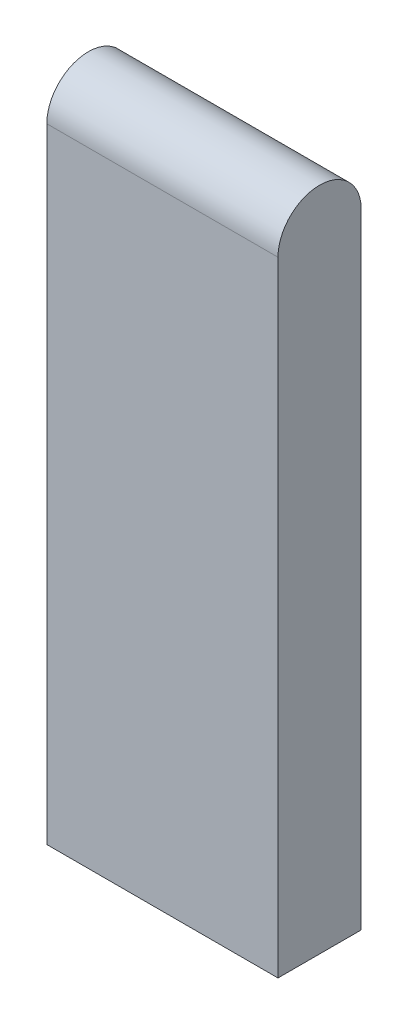
SolidWorks part; units mm, degrees
ref_plane "Front Plane" through (0, 0, 0) normal (0, 0, 1) x (1, 0, 0)
ref_plane "Top Plane" through (0, 0, 0) normal (0, 1, 0) x (1, 0, 0)
ref_plane "Right Plane" through (0, 0, 0) normal (1, 0, 0) x (0, 0, -1)
sketch "Sketch1" plane through (0, 0, 0) normal (1, 0, 0) x (0, 0, -1)
  line L2 (-9, 67.5) -> (-9, -67.5)
  line L3 (-9, -67.5) -> (9, -67.5)
  line L4 (9, 67.5) -> (9, -67.5)
  line L5 (-9, 67.5) -> (9, -67.5) construction
  line L6 (-9, -67.5) -> (9, 67.5) construction
  arc A0 (-9, 67.5) -> (9, 67.5) centre (0, 67.5) cw
  point P0 (0, 0)
  point P7 (0, 0)
  point P8 (0, 67.5)
  dimension "D1" = 18
  dimension "D2" = 135
extrude "Boss-Extrude1" add sketch "Sketch1" along normal mid plane 50
